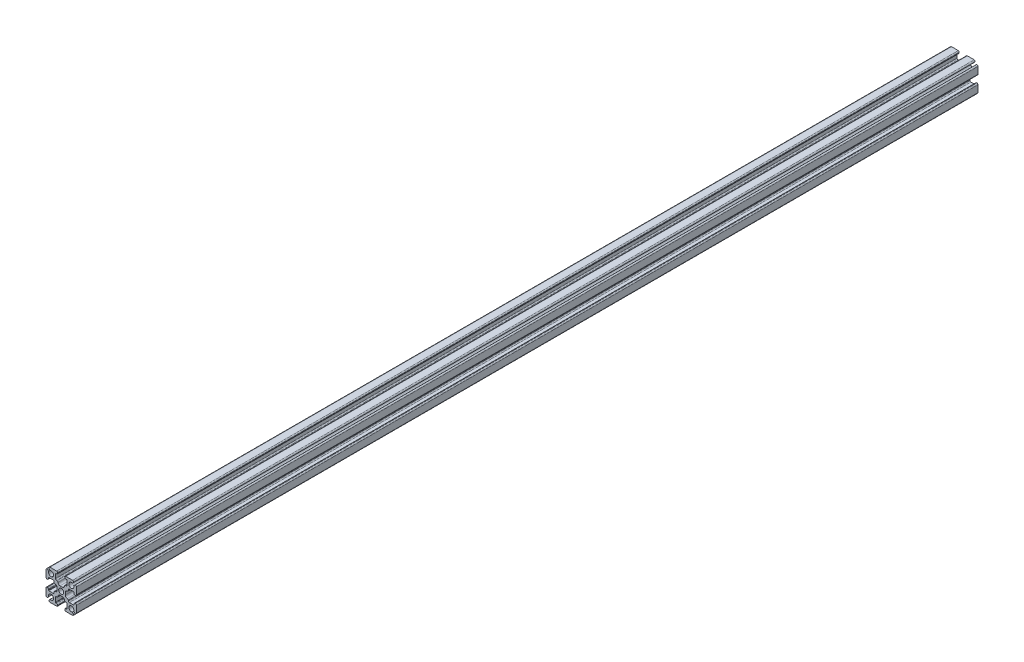
SolidWorks part; units mm, degrees
ref_plane "Front" through (0, 0, 0) normal (0, 0, 1) x (1, 0, 0)
ref_plane "Top" through (0, 0, 0) normal (0, 1, 0) x (1, 0, 0)
ref_plane "Right" through (0, 0, 0) normal (1, 0, 0) x (0, 0, -1)
sketch "Sketch1" plane through (0, 0, 0) normal (0, 0, 1) x (1, 0, 0)
  line L0 (6.6464, 5.9393) -> (6.1636, 5.4565)
  line L1 (5.4565, 6.1636) -> (5.9393, 6.6464)
  line L2 (5.5858, 7.5) -> (2.25, 7.5)
  line L3 (1.75, 7) -> (1.75, 6.8)
  line L4 (2.25, 6.3) -> (2.65, 6.3)
  line L5 (2.85, 6.1) -> (2.85, 4)
  line L6 (2.35, 3.5) -> (2.1, 3.5)
  line L7 (0.6, 2) -> (-0.6, 2)
  line L8 (-2.1, 3.5) -> (-2.35, 3.5)
  line L9 (-2.85, 4) -> (-2.85, 6.1)
  line L10 (-2.65, 6.3) -> (-2.25, 6.3)
  line L11 (-1.75, 6.8) -> (-1.75, 7)
  line L12 (-2.25, 7.5) -> (-5.5858, 7.5)
  line L13 (-5.9393, 6.6464) -> (-5.4565, 6.1636)
  line L14 (-6.1636, 5.4565) -> (-6.6464, 5.9393)
  line L15 (-7.5, 5.5858) -> (-7.5, 2.25)
  line L16 (-7, 1.75) -> (-6.8, 1.75)
  line L17 (-6.3, 2.25) -> (-6.3, 2.65)
  line L18 (-6.1, 2.85) -> (-4, 2.85)
  line L19 (-3.5, 2.35) -> (-3.5, 2.1)
  line L20 (-2, 0.6) -> (-2, -0.6)
  line L21 (-3.5, -2.1) -> (-3.5, -2.35)
  line L22 (-4, -2.85) -> (-6.1, -2.85)
  line L23 (-6.3, -2.65) -> (-6.3, -2.25)
  line L24 (-6.8, -1.75) -> (-7, -1.75)
  line L25 (-7.5, -2.25) -> (-7.5, -5.5858)
  line L26 (-6.6464, -5.9393) -> (-6.1636, -5.4565)
  line L27 (-5.4565, -6.1636) -> (-5.9393, -6.6464)
  line L28 (-5.5858, -7.5) -> (-2.25, -7.5)
  line L29 (-1.75, -7) -> (-1.75, -6.8)
  line L30 (-2.25, -6.3) -> (-2.65, -6.3)
  line L31 (-2.85, -6.1) -> (-2.85, -4)
  line L32 (-2.35, -3.5) -> (-2.1, -3.5)
  line L33 (-0.6, -2) -> (0.6, -2)
  line L34 (2.1, -3.5) -> (2.35, -3.5)
  line L35 (2.85, -4) -> (2.85, -6.1)
  line L36 (2.65, -6.3) -> (2.25, -6.3)
  line L37 (1.75, -6.8) -> (1.75, -7)
  line L38 (2.25, -7.5) -> (5.5858, -7.5)
  line L39 (5.9393, -6.6464) -> (5.4565, -6.1636)
  line L40 (6.1636, -5.4565) -> (6.6464, -5.9393)
  line L41 (7.5, -5.5858) -> (7.5, -2.25)
  line L42 (7, -1.75) -> (6.8, -1.75)
  line L43 (6.3, -2.25) -> (6.3, -2.65)
  line L44 (6.1, -2.85) -> (4, -2.85)
  line L45 (3.5, -2.35) -> (3.5, -2.1)
  line L46 (2, -0.6) -> (2, 0.6)
  line L47 (3.5, 2.1) -> (3.5, 2.35)
  line L48 (4, 2.85) -> (6.1, 2.85)
  line L49 (6.3, 2.65) -> (6.3, 2.25)
  line L50 (6.8, 1.75) -> (7, 1.75)
  line L51 (7.5, 2.25) -> (7.5, 5.5858)
  circle A0 centre (0, 0) radius 1.25
  arc A1 (6.1636, 5.4565) -> (5.4565, 6.1636) centre (5, 5) cw
  arc A2 (5.9393, 6.6464) -> (5.5858, 7.5) centre (5.5858, 7) ccw
  arc A3 (2.25, 7.5) -> (1.75, 7) centre (2.25, 7) ccw
  arc A4 (1.75, 6.8) -> (2.25, 6.3) centre (2.25, 6.8) ccw
  arc A5 (2.65, 6.3) -> (2.85, 6.1) centre (2.65, 6.1) cw
  arc A6 (2.85, 4) -> (2.35, 3.5) centre (2.35, 4) cw
  arc A7 (2.1, 3.5) -> (1.6, 3) centre (2.1, 3) ccw
  arc A8 (1.6, 3) -> (0.6, 2) centre (0.6, 3) cw
  arc A9 (-0.6, 2) -> (-1.6, 3) centre (-0.6, 3) cw
  arc A10 (-1.6, 3) -> (-2.1, 3.5) centre (-2.1, 3) ccw
  arc A11 (-2.35, 3.5) -> (-2.85, 4) centre (-2.35, 4) cw
  arc A12 (-2.85, 6.1) -> (-2.65, 6.3) centre (-2.65, 6.1) cw
  arc A13 (-2.25, 6.3) -> (-1.75, 6.8) centre (-2.25, 6.8) ccw
  arc A14 (-1.75, 7) -> (-2.25, 7.5) centre (-2.25, 7) ccw
  arc A15 (-5.5858, 7.5) -> (-5.9393, 6.6464) centre (-5.5858, 7) ccw
  arc A16 (-5.4565, 6.1636) -> (-6.1636, 5.4565) centre (-5, 5) cw
  arc A17 (-6.6464, 5.9393) -> (-7.5, 5.5858) centre (-7, 5.5858) ccw
  arc A18 (-7.5, 2.25) -> (-7, 1.75) centre (-7, 2.25) ccw
  arc A19 (-6.8, 1.75) -> (-6.3, 2.25) centre (-6.8, 2.25) ccw
  arc A20 (-6.3, 2.65) -> (-6.1, 2.85) centre (-6.1, 2.65) cw
  arc A21 (-4, 2.85) -> (-3.5, 2.35) centre (-4, 2.35) cw
  arc A22 (-3.5, 2.1) -> (-3, 1.6) centre (-3, 2.1) ccw
  arc A23 (-3, 1.6) -> (-2, 0.6) centre (-3, 0.6) cw
  arc A24 (-2, -0.6) -> (-3, -1.6) centre (-3, -0.6) cw
  arc A25 (-3, -1.6) -> (-3.5, -2.1) centre (-3, -2.1) ccw
  arc A26 (-3.5, -2.35) -> (-4, -2.85) centre (-4, -2.35) cw
  arc A27 (-6.1, -2.85) -> (-6.3, -2.65) centre (-6.1, -2.65) cw
  arc A28 (-6.3, -2.25) -> (-6.8, -1.75) centre (-6.8, -2.25) ccw
  arc A29 (-7, -1.75) -> (-7.5, -2.25) centre (-7, -2.25) ccw
  arc A30 (-7.5, -5.5858) -> (-6.6464, -5.9393) centre (-7, -5.5858) ccw
  arc A31 (-6.1636, -5.4565) -> (-5.4565, -6.1636) centre (-5, -5) cw
  arc A32 (-5.9393, -6.6464) -> (-5.5858, -7.5) centre (-5.5858, -7) ccw
  arc A33 (-2.25, -7.5) -> (-1.75, -7) centre (-2.25, -7) ccw
  arc A34 (-1.75, -6.8) -> (-2.25, -6.3) centre (-2.25, -6.8) ccw
  arc A35 (-2.65, -6.3) -> (-2.85, -6.1) centre (-2.65, -6.1) cw
  arc A36 (-2.85, -4) -> (-2.35, -3.5) centre (-2.35, -4) cw
  arc A37 (-2.1, -3.5) -> (-1.6, -3) centre (-2.1, -3) ccw
  arc A38 (-1.6, -3) -> (-0.6, -2) centre (-0.6, -3) cw
  arc A39 (0.6, -2) -> (1.6, -3) centre (0.6, -3) cw
  arc A40 (1.6, -3) -> (2.1, -3.5) centre (2.1, -3) ccw
  arc A41 (2.35, -3.5) -> (2.85, -4) centre (2.35, -4) cw
  arc A42 (2.85, -6.1) -> (2.65, -6.3) centre (2.65, -6.1) cw
  arc A43 (2.25, -6.3) -> (1.75, -6.8) centre (2.25, -6.8) ccw
  arc A44 (1.75, -7) -> (2.25, -7.5) centre (2.25, -7) ccw
  arc A45 (5.5858, -7.5) -> (5.9393, -6.6464) centre (5.5858, -7) ccw
  arc A46 (5.4565, -6.1636) -> (6.1636, -5.4565) centre (5, -5) cw
  arc A47 (6.6464, -5.9393) -> (7.5, -5.5858) centre (7, -5.5858) ccw
  arc A48 (7.5, -2.25) -> (7, -1.75) centre (7, -2.25) ccw
  arc A49 (6.8, -1.75) -> (6.3, -2.25) centre (6.8, -2.25) ccw
  arc A50 (6.3, -2.65) -> (6.1, -2.85) centre (6.1, -2.65) cw
  arc A51 (4, -2.85) -> (3.5, -2.35) centre (4, -2.35) cw
  arc A52 (3.5, -2.1) -> (3, -1.6) centre (3, -2.1) ccw
  arc A53 (3, -1.6) -> (2, -0.6) centre (3, -0.6) cw
  arc A54 (2, 0.6) -> (3, 1.6) centre (3, 0.6) cw
  arc A55 (3, 1.6) -> (3.5, 2.1) centre (3, 2.1) ccw
  arc A56 (3.5, 2.35) -> (4, 2.85) centre (4, 2.35) cw
  arc A57 (6.1, 2.85) -> (6.3, 2.65) centre (6.1, 2.65) cw
  arc A58 (6.3, 2.25) -> (6.8, 1.75) centre (6.8, 2.25) ccw
  arc A59 (7, 1.75) -> (7.5, 2.25) centre (7, 2.25) ccw
  arc A60 (7.5, 5.5858) -> (6.6464, 5.9393) centre (7, 5.5858) ccw
extrude "Boss-Extrude1" add sketch "Sketch1" along normal blind 444.5
